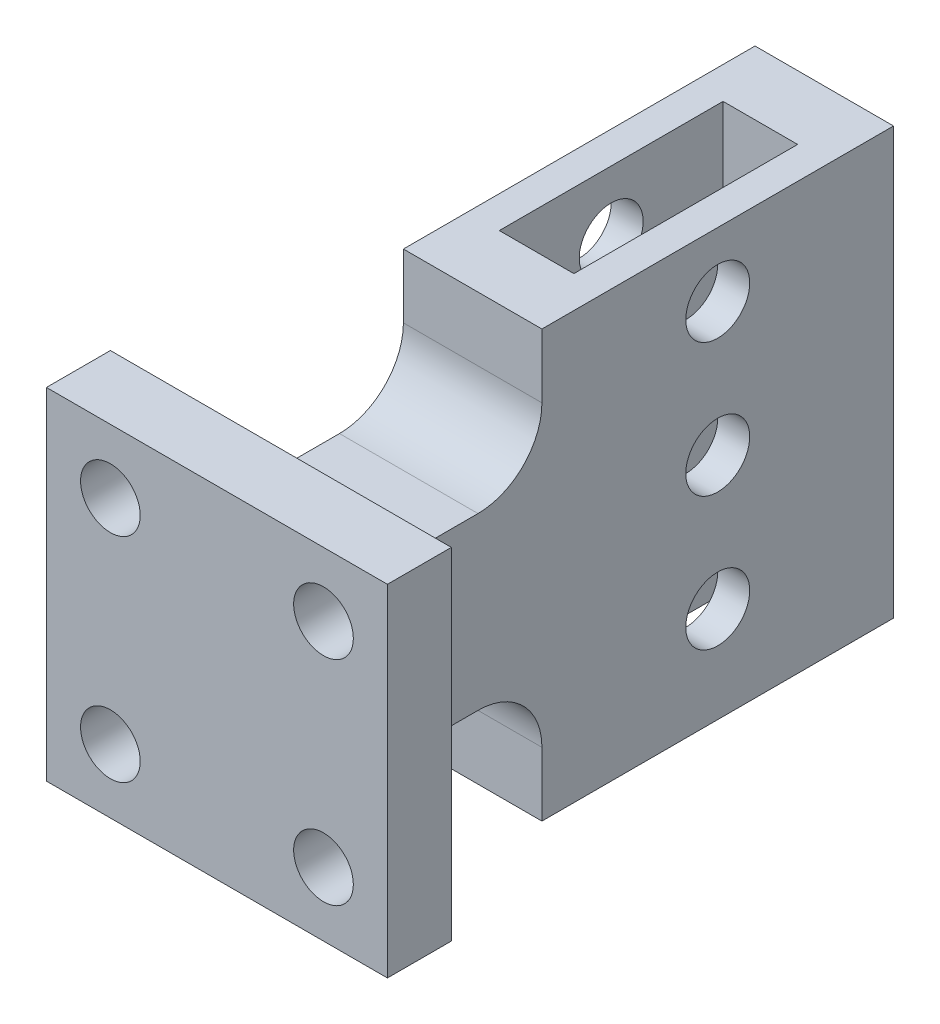
SolidWorks part; units mm, degrees
ref_plane "Front Plane" through (0, 0, 0) normal (0, 0, 1) x (1, 0, 0)
ref_plane "Top Plane" through (0, 0, 0) normal (0, 1, 0) x (1, 0, 0)
ref_plane "Right Plane" through (0, 0, 0) normal (1, 0, 0) x (0, 0, -1)
sketch "Sketch1" plane through (0, 0, 0) normal (0, 1, 0) x (1, 0, 0)
  line L1 (-3.25, 12.75) -> (3.25, 12.75)
  line L2 (-3.25, 12.75) -> (-3.25, -12.75)
  line L3 (-3.25, -12.75) -> (3.25, -12.75)
  line L4 (3.25, 12.75) -> (3.25, -12.75)
  line L5 (-3.25, 12.75) -> (3.25, -12.75) construction
  line L6 (-3.25, -12.75) -> (3.25, 12.75) construction
  line L7 (-8, -12.75) -> (8, -12.75)
  line L8 (-8, -12.75) -> (-8, -15.75)
  line L9 (-8, -15.75) -> (8, -15.75)
  line L10 (8, -12.75) -> (8, -15.75)
  line L11 (-1.75, 9.75) -> (1.75, 9.75)
  line L12 (-1.75, 9.75) -> (-1.75, -0.75)
  line L13 (-1.75, -0.75) -> (1.75, -0.75)
  line L14 (1.75, 9.75) -> (1.75, -0.75)
  line L15 (-1.75, 9.75) -> (1.75, -0.75) construction
  line L16 (-1.75, -0.75) -> (1.75, 9.75) construction
  point P0 (0, 0)
  point P10 (0, -12.75)
  point P11 (0, 4.5)
  point P16 (0, 0)
  dimension "D1" = 25.5
  dimension "D2" = 6.5
  dimension "D3" = 3
  dimension "D4" = 10.5
  dimension "D5" = 3.5
  dimension "D6" = 90
  dimension "D7" = 16
  dimension "D8" = 3
extrude "Boss-Extrude1" add sketch "Sketch1" along normal mid plane 20 contours L4 L1 L2 L3 L11 L14 L13 L12
sketch "Sketch2" plane through (0, 0, 0) normal (0, -1, 0) x (1, 0, 0)
  line L4 (-1.75, -9.75) -> (1.75, -9.75)
  line L5 (1.75, -9.75) -> (1.75, 0.75)
  line L6 (1.75, 0.75) -> (-1.75, 0.75)
  line L7 (-1.75, 0.75) -> (-1.75, -9.75)
  line L8 (-1.75, -9.75) -> (1.75, -9.75)
  line L9 (1.75, -9.75) -> (1.75, 0.75)
  line L10 (1.75, 0.75) -> (-1.75, 0.75)
  line L11 (-1.75, 0.75) -> (-1.75, -9.75)
  line L12 (-8, 12.75) -> (8, 12.75)
  line L13 (8, 12.75) -> (8, 15.75)
  line L14 (8, 15.75) -> (-8, 15.75)
  line L15 (-8, 15.75) -> (-8, 12.75)
  line L16 (-8, 12.75) -> (8, 12.75)
  line L17 (8, 12.75) -> (8, 15.75)
  line L18 (8, 15.75) -> (-8, 15.75)
  line L19 (-8, 15.75) -> (-8, 12.75)
  line L20 (-3.25, -12.75) -> (3.25, -12.75)
  line L21 (3.25, -12.75) -> (3.25, 12.75)
  line L22 (3.25, 12.75) -> (-3.25, 12.75)
  line L23 (-3.25, 12.75) -> (-3.25, -12.75)
  line L24 (-3.25, -12.75) -> (3.25, -12.75)
  line L25 (3.25, -12.75) -> (3.25, 12.75)
  line L26 (3.25, 12.75) -> (-3.25, 12.75)
  line L27 (-3.25, 12.75) -> (-3.25, -12.75)
  dimension "D1" = 0
  dimension "D2" = 0
  dimension "D3" = 0
extrude "Boss-Extrude2" add sketch "Sketch2" along normal mid plane 16
sketch "Sketch3" plane through (-3.25, 0, 0) normal (-1, 0, 0) x (0, 0, 1)
  line L0 (-12.75, -10) -> (12.75, -10) construction
  line L1 (12.75, 10) -> (3.75, 10)
  line L2 (12.75, 10) -> (12.75, -10)
  line L3 (12.75, -10) -> (3.75, -10)
  line L4 (3.75, 10) -> (3.75, -10)
  line L5 (-12.75, 10) -> (-12.75, -10) construction
  line L6 (12.75, 4) -> (3.75, 4)
  line L7 (12.75, 4) -> (12.75, -4)
  line L8 (12.75, -4) -> (3.75, -4)
  line L9 (3.75, 4) -> (3.75, -4)
  point P11 (12.75, 0)
  point P12 (0.9978, 3.458)
  line M10 (-12.75, -10) -> (12.75, -10)
  line M11 (12.75, -10) -> (12.75, -8)
  line M12 (12.75, -8) -> (12.75, 8)
  line M13 (12.75, 8) -> (12.75, 10)
  line M14 (12.75, 10) -> (-12.75, 10)
  dimension "D1" = 16.5
  dimension "D2" = 8
extrude "Cut-Extrude1" cut sketch "Sketch3" against normal up to next contours L8 L4 M12 M10 M11 | L6 L2 L4 M13 M14
sketch "Sketch4" plane through (0, 0, 15.75) normal (0, 0, 1) x (1, 0, 0)
  line L0 (-8, 8) -> (8, -8) construction
  line L1 (8, 8) -> (-8, -8) construction
  line L2 (0, 8) -> (0, -8) construction
  line L4 (8, 8) -> (-8, 8)
  line L5 (-8, 8) -> (-8, -8)
  line L6 (-8, -8) -> (8, -8)
  line L7 (8, -8) -> (8, 8)
  line L8 (8, 8) -> (-8, 8)
  line L9 (-8, 8) -> (-8, -8)
  line L10 (-8, -8) -> (8, -8)
  line L11 (8, -8) -> (8, 8)
  circle A0 centre (-5, 5) radius 1.4
  circle A1 centre (5, -5) radius 1.4
  circle A2 centre (-5, -5) radius 1.4
  circle A3 centre (5, 5) radius 1.4
  dimension "D2" = 2.8
  dimension "D3" = 10
  dimension "D1" = 0
extrude "Cut-Extrude2" cut sketch "Sketch4" against normal up to next contours A1 | A3 | A0 | A2
fillet "Fillet1" radius 3 2 edges at (0, 4, 3.75) (0, -4, 3.75)
sketch "Sketch5" plane through (-3.25, 0, 0) normal (-1, 0, 0) x (0, 0, 1)
sketch "Sketch6" plane through (3.25, 0, 0) normal (1, 0, 0) x (0, 0, -1)
  line L7 (12.75, 10) -> (12.75, -10) construction
  line L9 (12.75, 10) -> (-3.75, 10) construction
  line L10 (12.75, -10) -> (-3.75, -10) construction
  circle A2 centre (4.5, 7) radius 1.5
  circle A3 centre (4.5, -5.5) radius 1.5
  circle A4 centre (4.5, 0.75) radius 1.5
  dimension "D1" = 3
  dimension "D2" = 3
  dimension "D4" = 8.25
  dimension "D3" = 8.25
  dimension "D5" = 3
  dimension "D6" = 3
  dimension "D7" = 2
extrude "Cut-Extrude4" cut sketch "Sketch6" against normal through all
